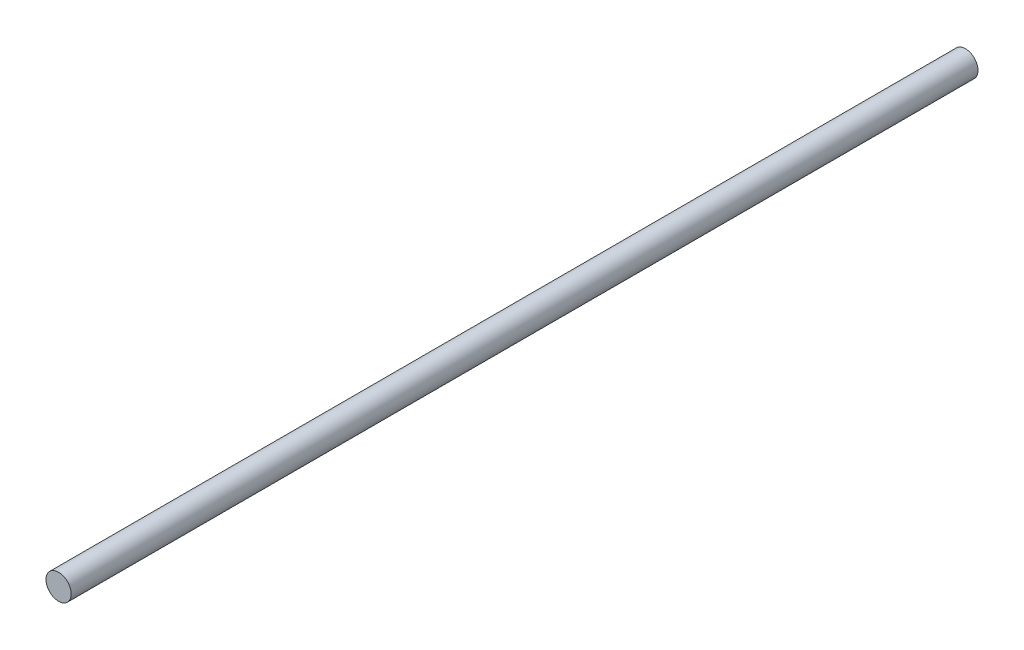
SolidWorks part; units mm, degrees
ref_plane "Front Plane" through (0, 0, 0) normal (0, 0, 1) x (1, 0, 0)
ref_plane "Top Plane" through (0, 0, 0) normal (0, 1, 0) x (1, 0, 0)
ref_plane "Right Plane" through (0, 0, 0) normal (1, 0, 0) x (0, 0, -1)
sketch "Sketch1" plane through (0, 0, 0) normal (0, 0, 1) x (1, 0, 0)
  circle A0 centre (0, 0) radius 3.175
  dimension "D1" = 6.35
extrude "Boss-Extrude1" add sketch "Sketch1" along normal blind 228.6
cosmetic thread "Cosmetic Thread3" parameters "D2"=5.268
